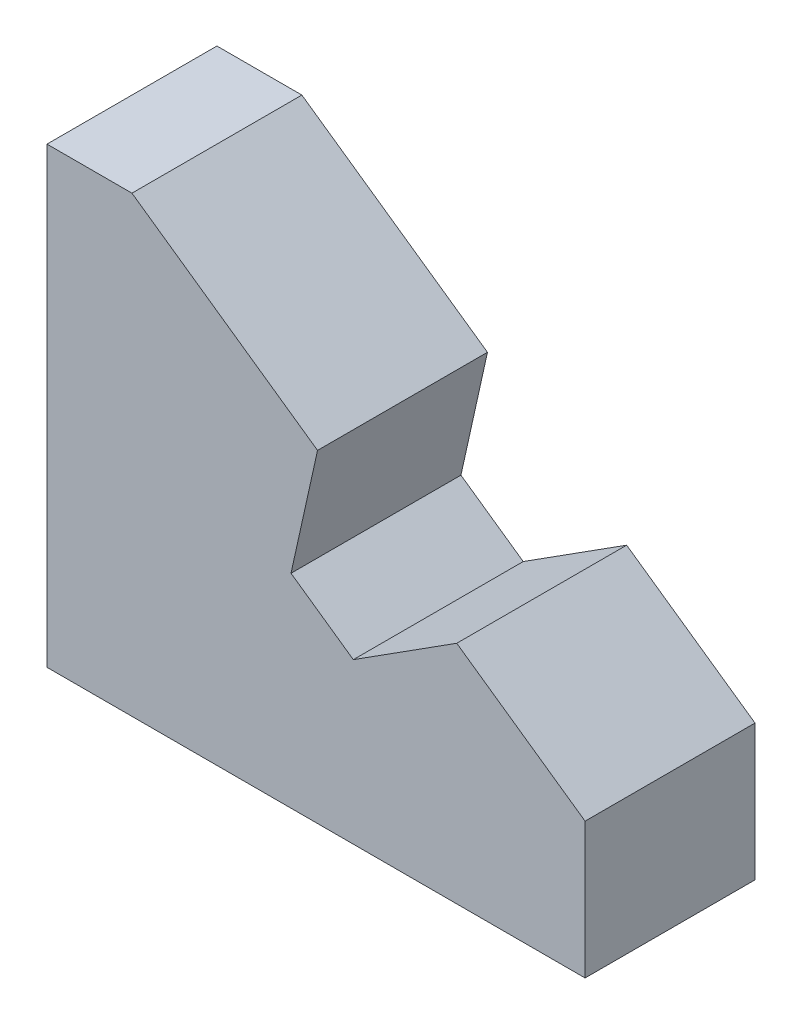
SolidWorks part; units mm, degrees
ref_plane "Front Plane" through (0, 0, 0) normal (0, 0, 1) x (1, 0, 0)
ref_plane "Top Plane" through (0, 0, 0) normal (0, 1, 0) x (1, 0, 0)
ref_plane "Right Plane" through (0, 0, 0) normal (1, 0, 0) x (0, 0, -1)
sketch "Sketch5" plane through (0, 0, 0) normal (0, 0, 1) x (1, 0, 0)
  line L0 (0, 0) -> (0, 80)
  line L1 (0, -44) -> (0, 44) construction
  line L2 (0, 80) -> (15, 80)
  line L3 (15, 80) -> (47.7661, 57.0569)
  line L4 (95, 23.9834) -> (95, 0)
  line L5 (52.25, 0) -> (-52.25, 0) construction
  line L6 (95, 0) -> (0, 0)
  line L7 (60.0534, 48.4533) -> (48.5818, 32.0703) construction
  line L8 (47.7661, 57.0569) -> (43.0806, 35.9222)
  line L9 (43.0806, 35.9222) -> (54.083, 28.2183)
  line L10 (54.083, 28.2183) -> (72.3406, 39.8496)
  line L11 (72.3406, 39.8496) -> (95, 23.9834)
  point P16 (0, 61.705)
  point P17 (48.5818, 32.0703)
  point P18 (0, 0)
  point P19 (0, 0)
  point P20 (45.1068, 39.0011)
  point P21 (52.1885, 39.788)
  point P22 (71.8599, 44.8239)
  point P23 (92.1609, 25.9393)
  point P24 (33.776, 39.9454)
  point P25 (39.5297, 62.2041)
  point P26 (39.5297, 36.3173)
  point P27 (47.1916, 56.4019)
  point P28 (0, 0)
  point P29 (48.5818, 32.0703)
  dimension "D1" = 95
  dimension "D2" = 80
  dimension "D3" = 15
  dimension "D4" = 55
  dimension "D5" = 45
  dimension "D6" = 30
  dimension "D7" = 20
  dimension "D8" = 35
extrude "Boss-Extrude1" add sketch "Sketch5" along normal blind 30 contours L11 L4 L6 L0 L2 L3 L8 L9 L10
